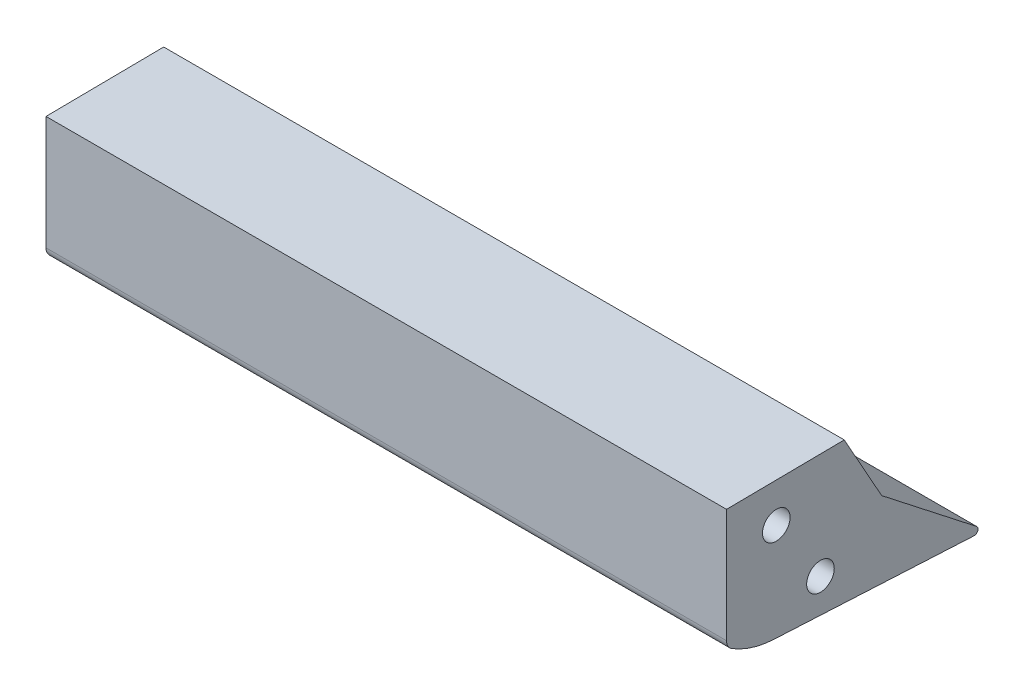
SolidWorks part; units mm, degrees
ref_plane "Front Plane" through (0, 0, 0) normal (0, 0, 1) x (1, 0, 0)
ref_plane "Top Plane" through (0, 0, 0) normal (0, 1, 0) x (1, 0, 0)
ref_plane "Right Plane" through (0, 0, 0) normal (1, 0, 0) x (0, 0, -1)
sketch "Sketch1" plane through (0, 0, 0) normal (1, 0, 0) x (0, 0, -1)
  line L0 (-4.25, 0) -> (-4.25, -4)
  line L1 (-1.45, -21.2) -> (22.05, -21.2)
  line L3 (22.05, -21.2) -> (12.5939, -13.8121)
  line L4 (12.5939, -13.8121) -> (3.7093, 2.0744)
  line L5 (-161.4, -23) -> (38.6, -23) construction
  line L6 (-3.7566, -5.1121) -> (-1.9434, -6.7534)
  line L7 (-1.45, -7.8655) -> (-1.45, -21.2)
  circle A0 centre (0, 0) radius 2.15
  arc A1 (3.7093, 2.0744) -> (-4.25, 0) centre (0, 0) ccw
  arc A2 (-4.25, -4) -> (-3.7566, -5.1121) centre (-2.75, -4) ccw
  arc A3 (-1.45, -7.8655) -> (-1.9434, -6.7534) centre (-2.95, -7.8655) ccw
  point P16 (-1.45, -7.2)
  dimension "D1" = 4.3
  dimension "D2" = 8.5
  dimension "D8" = 21.2
  dimension "D3" = 1.5
  dimension "D4" = 14
  dimension "D10" = 1.5
  dimension "D5" = 38
  dimension "D6" = 12
  dimension "D7" = 1.8
  dimension "D9" = 2.8
  dimension "D11" = 4
  dimension "D12" = 23.5
extrude "Boss-Extrude1" add sketch "Sketch1" along normal mid plane 62.6
sketch "Sketch2" plane through (0, 0, 4.25) normal (0, 0, 1) x (1, 0, 0)
  line L0 (31.3, 4.25) -> (-31.3, 4.25) construction
  line L1 (-28.8, 4.25) -> (28.8, 4.25)
  line L2 (-28.8, 4.25) -> (-28.8, -7.75)
  line L3 (-28.8, -7.75) -> (28.8, -7.75)
  line L4 (28.8, 4.25) -> (28.8, -7.75)
  line L5 (-31.3, 0) -> (-31.3, -4) construction
  line L6 (31.3, 0) -> (31.3, -4) construction
  dimension "D1" = 2.5
  dimension "D2" = 2.5
  dimension "D3" = 12
extrude "Cut-Extrude1" cut sketch "Sketch2" against normal up to next
sketch "Sketch8" plane through (31.3, 0, 0) normal (1, 0, 0) x (0, 0, -1)
  line L0 (-1.45, -7.8655) -> (9.2037, -7.75)
  line L1 (-3.7566, -5.1121) -> (-1.9434, -6.7534) construction
  line L2 (-4.25, 0) -> (-4.25, -4) construction
  line L3 (12.5939, -13.8121) -> (3.7093, 2.0744) construction
  line L4 (-3.7566, -5.1121) -> (-1.9434, -6.7534)
  line L5 (-4.25, 0) -> (-4.25, -4)
  line L6 (9.2037, -7.75) -> (3.7093, 2.0744)
  arc A0 (-1.45, -7.8655) -> (-1.9434, -6.7534) centre (-2.95, -7.8655) ccw construction
  arc A1 (-4.25, -4) -> (-3.7566, -5.1121) centre (-2.75, -4) ccw construction
  arc A2 (3.7093, 2.0744) -> (-4.25, 0) centre (0, 0) ccw construction
  arc A3 (-1.45, -7.8655) -> (-1.9434, -6.7534) centre (-2.95, -7.8655) ccw
  arc A4 (-4.25, -4) -> (-3.7566, -5.1121) centre (-2.75, -4) ccw
  arc A5 (3.7093, 2.0744) -> (-4.25, 0) centre (0, 0) ccw
extrude "Cut-Extrude3" cut sketch "Sketch8" against normal through all
fillet "Fillet1" [suppressed] radius 2
sketch "Sketch9" plane through (0, -7.8518, 0.19) normal (0, 0.9999, 0.0108) x (1, 0, 0)
  line L0 (31.3, -1.26) -> (31.3, 9.3943) construction
  line L1 (-30.8, -25.5438) -> (30.8, -25.5438)
  line L2 (-30.8, -25.5438) -> (-30.8, 26.0941)
  line L3 (-30.8, 26.0941) -> (30.8, 26.0941)
  line L4 (30.8, -25.5438) -> (30.8, 26.0941)
  line L5 (-30.8, -25.5438) -> (30.8, 26.0941) construction
  line L6 (-30.8, 26.0941) -> (30.8, -25.5438) construction
  line L7 (-31.3, -26.5438) -> (31.3, -26.5438)
  line L8 (-31.3, -26.5438) -> (-31.3, 27.0941)
  line L9 (-31.3, 27.0941) -> (31.3, 27.0941)
  line L10 (31.3, -26.5438) -> (31.3, 27.0941)
  line L11 (-31.3, -26.5438) -> (31.3, 27.0941) construction
  line L12 (-31.3, 27.0941) -> (31.3, -26.5438) construction
  line L13 (31.3, 22.0941) -> (-31.3, 22.0941) construction
  point P0 (0, 0.2751)
  point P6 (0, 0.2751)
  dimension "D1" = 1
  dimension "D2" = 5
  dimension "D3" = 0.5
extrude "Cut-Extrude4" cut sketch "Sketch9" against normal through all and the other way through all
sketch "Sketch10" plane through (30.8, 0, 0) normal (1, 0, 0) x (0, 0, -1)
  line L1 (-1.45, -7.8655) -> (-1.45, -21.2) construction
  circle A0 centre (3.05, -11.3655) radius 1.25
  circle A1 centre (7.05, -17.3655) radius 1.25
  dimension "D1" = 2.5
  dimension "D2" = 3.5
  dimension "D3" = 6
  dimension "D4" = 4.5
  dimension "D5" = 4
extrude "Cut-Extrude5" cut sketch "Sketch10" against normal blind 12
sketch "Sketch11" plane through (-30.8, 0, 0) normal (-1, 0, 0) x (0, 0, 1)
  circle A1 centre (-7.05, -17.3655) radius 1.25
  circle A2 centre (-7.05, -17.3655) radius 1.25
  circle A3 centre (-3.05, -11.3655) radius 1.25
  circle A4 centre (-3.05, -11.3655) radius 1.25
  dimension "D1" = 0
  dimension "D2" = 0
extrude "Cut-Extrude6" cut sketch "Sketch11" against normal blind 12
sketch "Esboço1" plane through (30.8, 0, 0) normal (1, 0, 0) x (0, 0, -1)
  line L0 (-1.45, -21.2) -> (22.05, -21.2) construction
  line L1 (-1.45, -7.8655) -> (-1.45, -21.2) construction
  line L2 (-1.45, -21.2) -> (22.05, -21.2)
  line L3 (-1.45, -18.7) -> (-1.45, -21.2)
  line L4 (22.05, -21.2) -> (2.8134, -20.2)
  arc A0 (2.8134, -20.2) -> (-1.45, -18.7) centre (3.2287, -12.2108) cw
  dimension "D2" = 8
  dimension "D1" = 1
  dimension "D3" = 2.5
extrude "Corte-extrusão1" cut sketch "Esboço1" against normal through all
fillet "Filete1" radius 1 1 edges at (0, -18.7, 1.45)
fillet "Filete2" radius 0.35 1 edges at (0, -21.2, -22.05)
